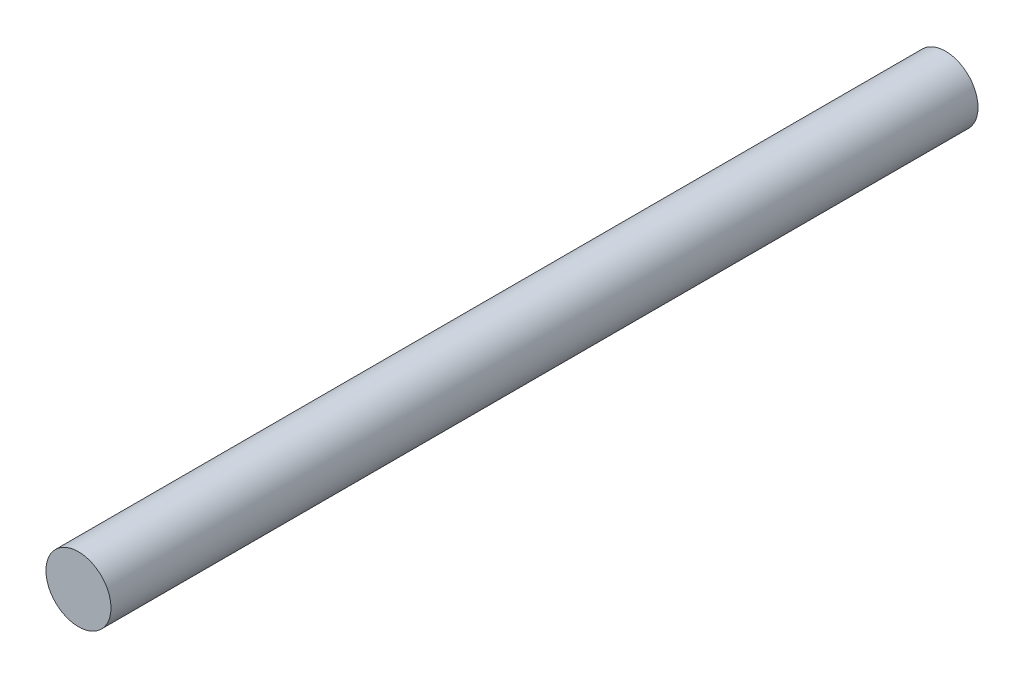
SolidWorks part; units mm, degrees
ref_plane "Front Plane" through (0, 0, 0) normal (0, 0, 1) x (1, 0, 0)
ref_plane "Top Plane" through (0, 0, 0) normal (0, 1, 0) x (1, 0, 0)
ref_plane "Right Plane" through (0, 0, 0) normal (1, 0, 0) x (0, 0, -1)
sketch "Sketch1" plane through (0, 0, 0) normal (0, 0, 1) x (1, 0, 0)
  circle A0 centre (0, 0) radius 37.5
  dimension "D1" = 75
extrude "Boss-Extrude1" add sketch "Sketch1" along normal blind 1000
